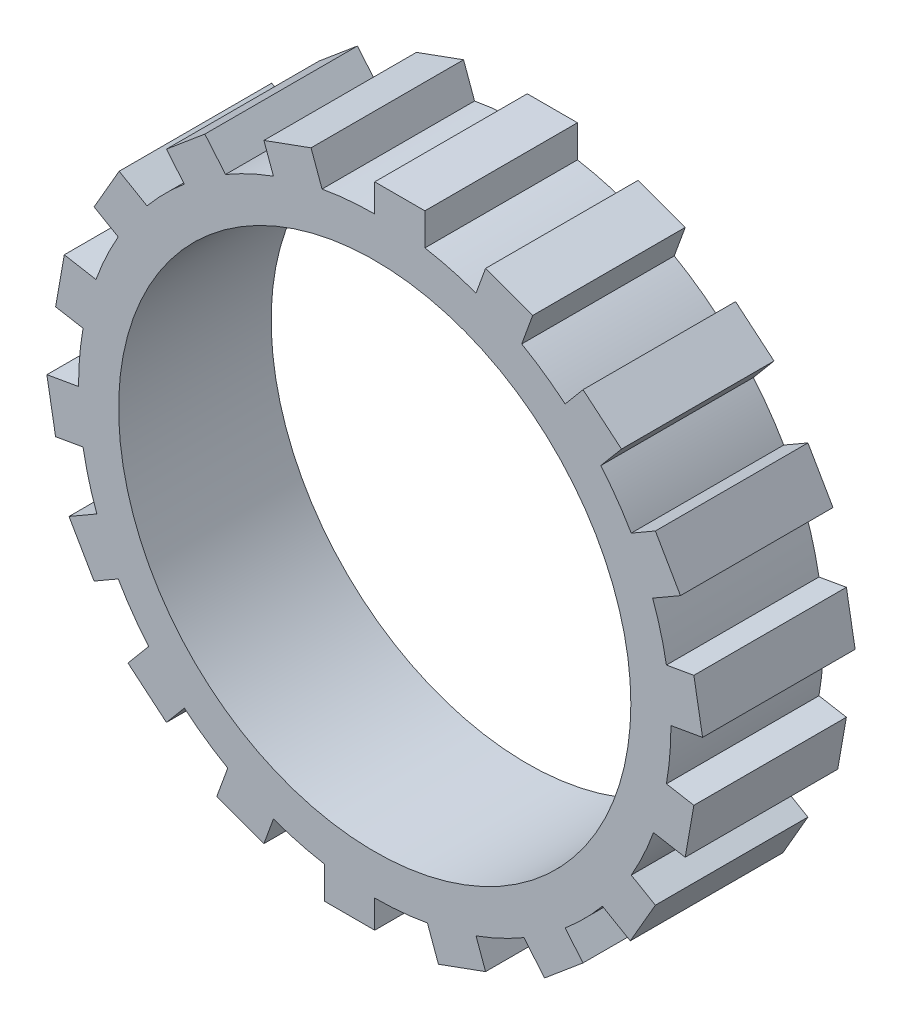
SolidWorks part; units mm, degrees
ref_plane "Front Plane" through (0, 0, 0) normal (0, 0, 1) x (1, 0, 0)
ref_plane "Top Plane" through (0, 0, 0) normal (0, 1, 0) x (1, 0, 0)
ref_plane "Right Plane" through (0, 0, 0) normal (1, 0, 0) x (0, 0, -1)
sketch "Sketch1" plane through (0, 0, 0) normal (0, 0, 1) x (1, 0, 0)
  circle A0 centre (0, 0) radius 7.35
  circle A1 centre (0, 0) radius 8.5
  dimension "D1" = 14.7
  dimension "D2" = 17
extrude "Boss-Extrude3" add sketch "Sketch1" along normal blind 8.755
ref_plane "Plane1" through (0, 8.5, 0) normal (0, 1, 0) x (1, 0, 0)
sketch "Sketch3" plane through (0, 8.5, 0) normal (0, 1, 0) x (1, 0, 0)
  line L0 (0, -8.755) -> (0, 0) construction
  line L1 (-8.5, -8.755) -> (8.5, -8.755) construction
  line L3 (0, -4.3775) -> (1.4399, -4.3775)
  line L4 (0, -4.3775) -> (0, -8.755)
  line L5 (0, -8.755) -> (1.4399, -8.755)
  line L6 (1.4399, -4.3775) -> (1.4399, -8.755)
extrude "Boss-Extrude5" add sketch "Sketch3" against normal blind 0.3 and the other way blind 0.8
pattern_circular "CirPattern1" count 18 over 360 about axis through (0, 0, 0) along (0, 0, 1) of "Boss-Extrude5"
sketch "Sketch6" plane through (0, 0, 0) normal (0, 0, -1) x (-1, 0, 0)
  circle A0 centre (0, 0) radius 8.5
extrude "Cut-Extrude1" cut sketch "Sketch6" against normal up to surface (4.3775 mm away) up to face at (-7.3274, 5.0626, 4.3775)
